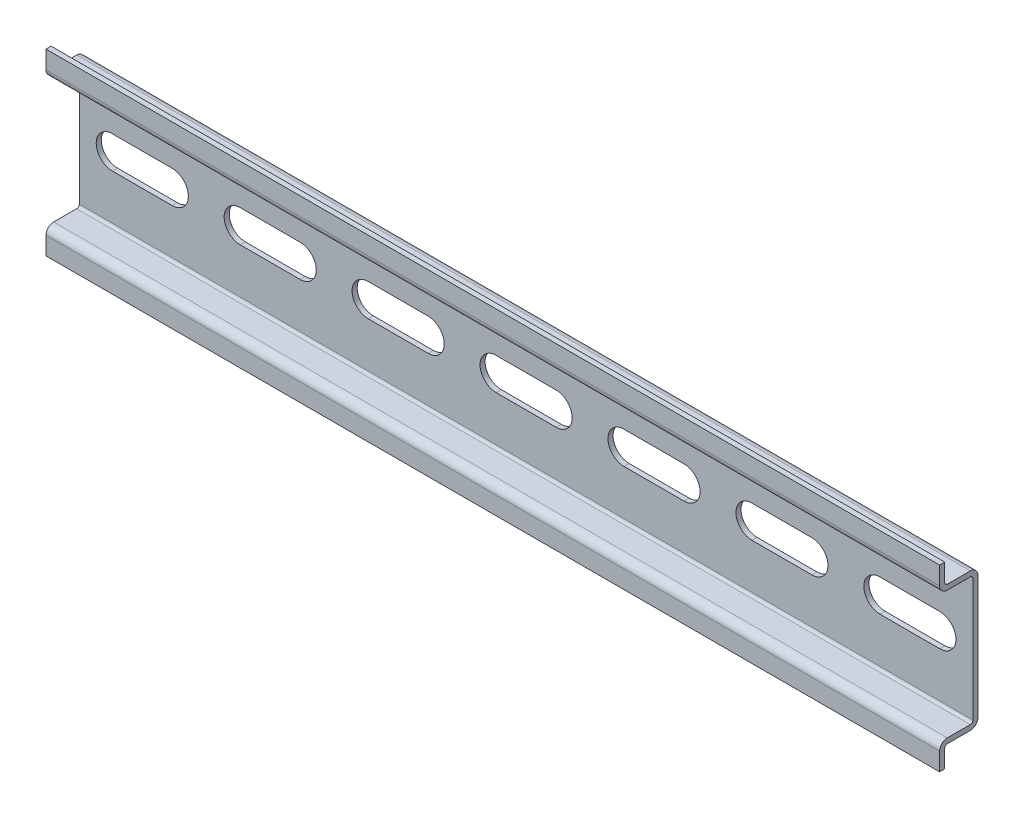
SolidWorks part; units mm, degrees
ref_plane "Front Plane" through (0, 0, 0) normal (0, 0, 1) x (1, 0, 0)
ref_plane "Top Plane" through (0, 0, 0) normal (0, 1, 0) x (1, 0, 0)
ref_plane "Right Plane" through (0, 0, 0) normal (1, 0, 0) x (0, 0, -1)
sketch "Sketch1" plane through (0, 0, 0) normal (0, 0, 1) x (1, 0, 0)
  line L0 (-87.3125, 0) -> (87.3125, 0) construction
  line L1 (-87.3125, 0) -> (-87.3125, 17.5)
  line L2 (-87.3125, 17.5) -> (87.3125, 17.5)
  line L3 (87.3125, 17.5) -> (87.3125, 0)
  line L4 (-87.3125, 13.5) -> (87.3125, 13.5)
  line L5 (0, 0) -> (0, 17.5) construction
  line L8 (-5.85, 3.15) -> (5.85, 3.15)
  line L9 (-5.85, -3.15) -> (5.85, -3.15)
  line L10 (19.15, 3.15) -> (30.85, 3.15)
  line L19 (19.15, -3.15) -> (30.85, -3.15)
  line L27 (44.15, 3.15) -> (55.85, 3.15)
  line L28 (44.15, -3.15) -> (55.85, -3.15)
  line L29 (69.15, 3.15) -> (80.85, 3.15)
  line L30 (69.15, -3.15) -> (80.85, -3.15)
  arc A2 (-5.85, 3.15) -> (-5.85, -3.15) centre (-5.85, 0) ccw
  arc A3 (5.85, -3.15) -> (5.85, 3.15) centre (5.85, 0) ccw
  arc A12 (30.85, -3.15) -> (30.85, 3.15) centre (30.85, 0) ccw
  arc A13 (19.15, 3.15) -> (19.15, -3.15) centre (19.15, 0) ccw
  arc A14 (55.85, -3.15) -> (55.85, 3.15) centre (55.85, 0) ccw
  arc A15 (44.15, 3.15) -> (44.15, -3.15) centre (44.15, 0) ccw
  arc A16 (80.85, -3.15) -> (80.85, 3.15) centre (80.85, 0) ccw
  arc A17 (69.15, 3.15) -> (69.15, -3.15) centre (69.15, 0) ccw
  point P8 (-9, 0)
  point P12 (9, 0)
  point P17 (0, 3.15)
  point P26 (25, 3.15)
  point P31 (50, -3.15)
  point P32 (25, -3.15)
  point P34 (0, -3.15)
  dimension "Length" = 174.625
  dimension "Height" = 35
  dimension "Height 2" = 27
  dimension "Mounting Hole Length" = 18
  dimension "Mounting Hole Dia" = 6.3
  dimension "Mounting Hole Center to Center" = 25
  dimension "No. Holes" = 4
sketch "Sketch2" plane through (0, 0, 0) normal (1, 0, 0) x (0, 0, -1)
  line L0 (0, 0) -> (0, 17.5) construction
  line L1 (0, 0) -> (0, 17.5) construction
  line L2 (-3.75, 0) -> (3.75, 0) construction
  line L3 (3.75, 0) -> (3.75, 13.5)
  line L4 (3.75, 13.5) -> (-2.75, 13.5)
  line L5 (-3.75, 0) -> (-3.75, 17.5) construction
  line L6 (-3.75, 17.5) -> (3.75, 17.5) construction
  line L7 (3.75, 17.5) -> (3.75, 0) construction
  line L8 (-2.75, 13.5) -> (-2.75, 17.5)
  dimension "Depth" = 7.5
  dimension "Sheet Metal Thickness" = 1
sketch "Sketch3" plane through (0, 0, 0) normal (1, 0, 0) x (0, 0, -1)
  line L0 (-2.75, 13.5) -> (-2.75, 17.5) construction
  line L1 (3.75, 13.5) -> (-2.75, 13.5) construction
  line L2 (3.75, 0) -> (3.75, 13.5) construction
  line L3 (-2.75, 13.5) -> (-2.75, 17.5)
  line L4 (3.75, 13.5) -> (-2.75, 13.5)
  line L5 (3.75, -13.5) -> (3.75, 13.5)
  line L6 (-3.75, 0) -> (3.75, 0) construction
  line L7 (-3.75, 0) -> (3.75, 0) construction
  line L8 (-2.75, -13.5) -> (-2.75, -17.5)
  line L9 (3.75, -13.5) -> (-2.75, -13.5)
extrude "Extrude-Thin1" add sketch "Sketch3" along normal up to vertex (87.3125 mm away) and the other way up to vertex (87.3125 mm away) thin up to point (87.3125, 0, 0) other way up to point (-87.3125, 0, 0) thin type one direction wall 1
sketch "Sketch4" plane through (0, 0, 0) normal (0, 0, 1) x (1, 0, 0)
  line L0 (-5.85, -3.15) -> (5.85, -3.15) construction
  line L1 (-5.85, 3.15) -> (5.85, 3.15) construction
  line L2 (-5.85, -3.15) -> (5.85, -3.15)
  line L3 (-5.85, 3.15) -> (5.85, 3.15)
  arc A0 (-5.85, 3.15) -> (-5.85, -3.15) centre (-5.85, 0) ccw construction
  arc A1 (5.85, -3.15) -> (5.85, 3.15) centre (5.85, 0) ccw construction
  arc A2 (-5.85, 3.15) -> (-5.85, -3.15) centre (-5.85, 0) ccw
  arc A3 (5.85, -3.15) -> (5.85, 3.15) centre (5.85, 0) ccw
extrude "Cut-Extrude1" cut sketch "Sketch4" against normal through all
pattern_linear "LPattern1" count 4 spacing 25 along (1, 0, 0) count 4 spacing 25 along (-1, 0, 0) of "Cut-Extrude1"
equation "\"D3@LPattern1\" = \"Mounting Hole Center to Center@Sketch1\""
equation "\"D4@LPattern1\" = \"Mounting Hole Center to Center@Sketch1\""
equation "\"D1@LPattern1\" = \"No. Holes@Sketch1\""
equation "\"D2@LPattern1\" = \"No. Holes@Sketch1\""
